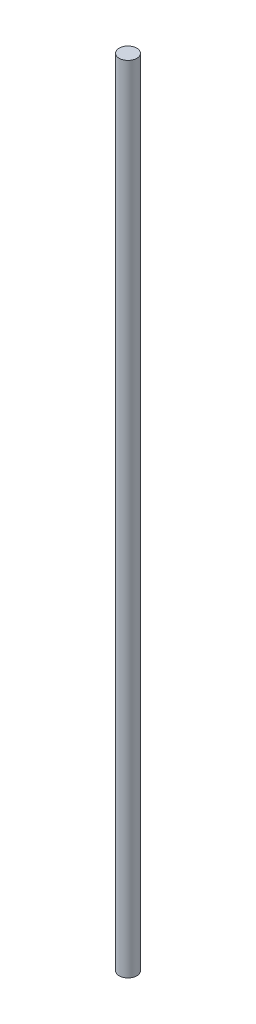
SolidWorks part; units mm, degrees
material "Chrome Stainless Steel"
ref_plane "Front Plane" through (0, 0, 0) normal (0, 0, 1) x (1, 0, 0)
ref_plane "Top Plane" through (0, 0, 0) normal (0, 1, 0) x (1, 0, 0)
ref_plane "Right Plane" through (0, 0, 0) normal (1, 0, 0) x (0, 0, -1)
sketch "Sketch1" plane through (0, 0, 0) normal (0, 1, 0) x (1, 0, 0)
  circle A0 centre (0, 0) radius 5
  dimension "D1" = 10
extrude "Boss-Extrude1" add sketch "Sketch1" along normal blind 450
